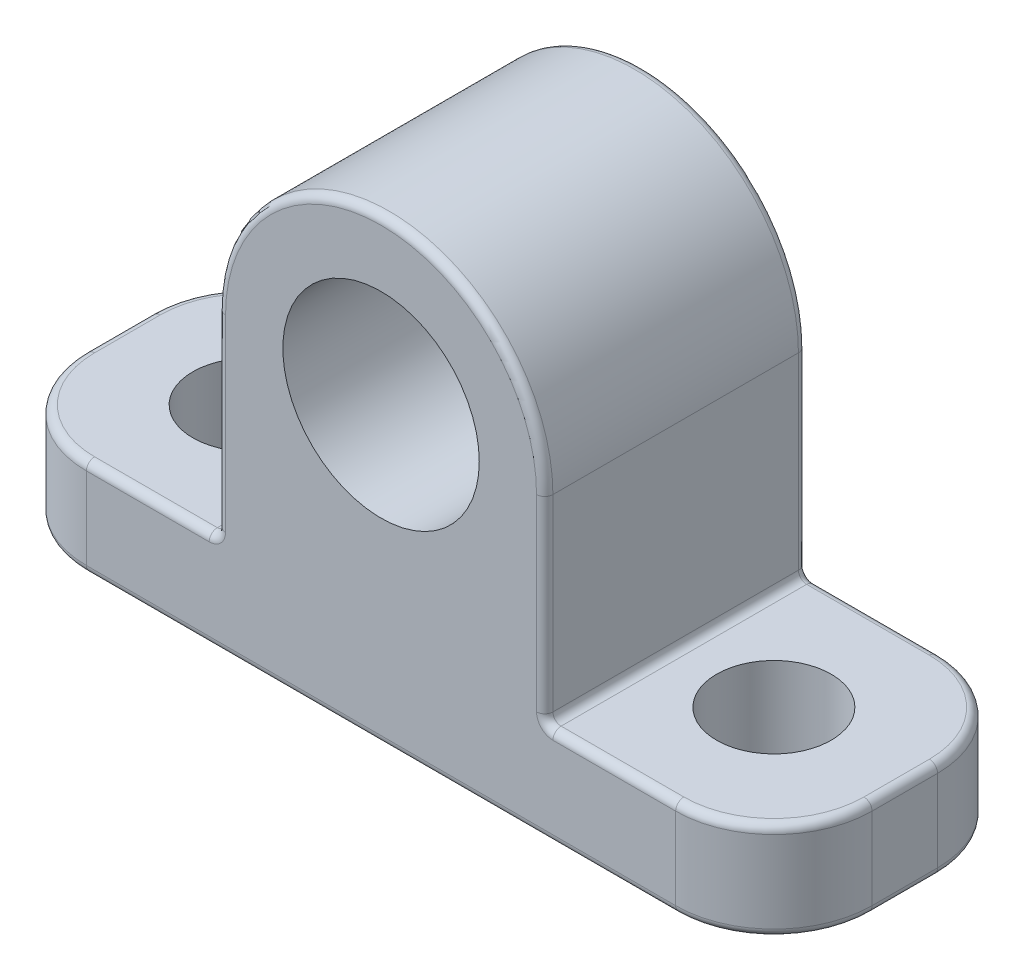
SolidWorks part; units mm, degrees
ref_plane "Front Plane" through (0, 0, 0) normal (0, 0, 1) x (1, 0, 0)
ref_plane "Top Plane" through (0, 0, 0) normal (0, 1, 0) x (1, 0, 0)
ref_plane "Right Plane" through (0, 0, 0) normal (1, 0, 0) x (0, 0, -1)
sketch "Sketch1" plane through (0, 0, 0) normal (0, 0, 1) x (1, 0, 0)
  line L0 (-12, 0) -> (12, 0)
  line L1 (12, 0) -> (12, 3)
  line L2 (12, 3) -> (5, 3)
  line L3 (5, 3) -> (5, 9)
  line L4 (-5, 9) -> (-5, 3)
  line L5 (-5, 3) -> (-12, 3)
  line L6 (-12, 3) -> (-12, 0)
  arc A0 (5, 9) -> (-5, 9) centre (0, 9) ccw
  circle A1 centre (0, 9) radius 3
  point P11 (0, 0)
  point P12 (0, 0)
  dimension "D4" = 6
  dimension "D5" = 5
  dimension "D1" = 24
  dimension "D2" = 3
  dimension "D3" = 6
extrude "Boss-Extrude1" add sketch "Sketch1" against normal blind 8
sketch "Sketch2" plane through (0, 3, 0) normal (0, 1, 0) x (1, 0, 0)
  line L0 (-12, 8) -> (-12, 0) construction
  line L1 (-8, 8) -> (-9, 8)
  line L2 (-5, 8) -> (-12, 8) construction
  line L3 (-12, 5) -> (-12, 3)
  line L5 (-9, 0) -> (-8, 0)
  line L6 (-5, 0) -> (-12, 0) construction
  line L7 (0, 11.1089) -> (0, -5.0846) construction
  line L8 (8, 8) -> (9, 8)
  line L9 (12, 5) -> (12, 3)
  line L10 (9, 0) -> (8, 0)
  line L11 (8, 8) -> (-8, 8)
  line L12 (-8, 0) -> (8, 0)
  circle A0 centre (8, 4) radius 1.75
  circle A1 centre (-8, 4) radius 1.75
  arc A2 (-9, 8) -> (-12, 5) centre (-9, 5) ccw
  arc A3 (-12, 3) -> (-9, 0) centre (-9, 3) ccw
  arc A4 (9, 8) -> (12, 5) centre (9, 5) cw
  arc A5 (12, 3) -> (9, 0) centre (9, 3) cw
  point P6 (-12, 4)
  dimension "D1" = 8
  dimension "D3" = 3.5
  dimension "D4" = 3
  dimension "D2" = 8
extrude "Cut-Extrude1" cut sketch "Sketch2" against normal blind 8 flip side to cut
fillet "Fillet1" radius 0.25 28 edges at (-5, 6, -8) (0, 14, -8) (5, 6, 0) (-5, 6, 0) (7, 3, -8) (11.1213, 3, -7.1213) (12, 3, -4) (11.1213, 3, -0.8787) (-7, 3, -8) (-11.1213, 3, -7.1213) (-12, 3, -4) (5, 6, -8) (0, 14, 0) (7, 3, 0) (-11.1213, 3, -0.8787) (-7, 3, 0) (5, 3, -4) (-11.1213, 0, -7.1213) (-12, 0, -4) (-11.1213, 0, -0.8787) (0, 0, 0) (11.1213, 0, -0.8787) (12, 0, -4) (11.1213, 0, -7.1213) (0, 0, -8) (9.75, 0, -4) (-6.25, 0, -4) (-5, 3, -4)
